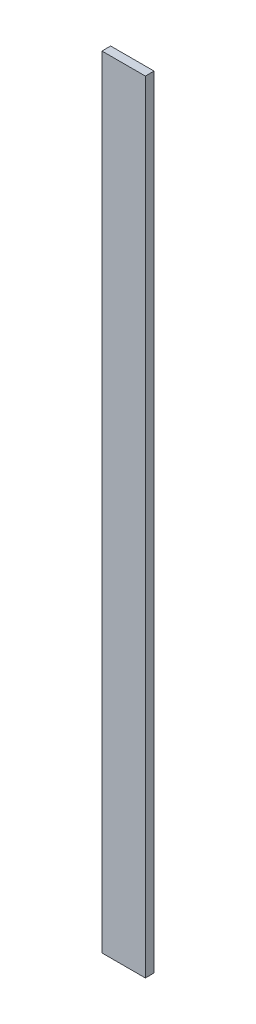
SolidWorks part; units mm, degrees
ref_plane "Front Plane" through (0, 0, 0) normal (0, 0, 1) x (1, 0, 0)
ref_plane "Top Plane" through (0, 0, 0) normal (0, 1, 0) x (1, 0, 0)
ref_plane "Right Plane" through (0, 0, 0) normal (1, 0, 0) x (0, 0, -1)
sketch "Sketch1" plane through (0, 0, 0) normal (0, 1, 0) x (1, 0, 0)
  line L1 (-25, -5) -> (25, -5)
  line L2 (-25, -5) -> (-25, 5)
  line L3 (-25, 5) -> (25, 5)
  line L4 (25, -5) -> (25, 5)
  line L5 (-25, -5) -> (25, 5) construction
  line L6 (-25, 5) -> (25, -5) construction
  point P0 (0, 0)
  dimension "D1" = 10
  dimension "D2" = 50
extrude "Boss-Extrude1" add sketch "Sketch1" along normal blind 900
